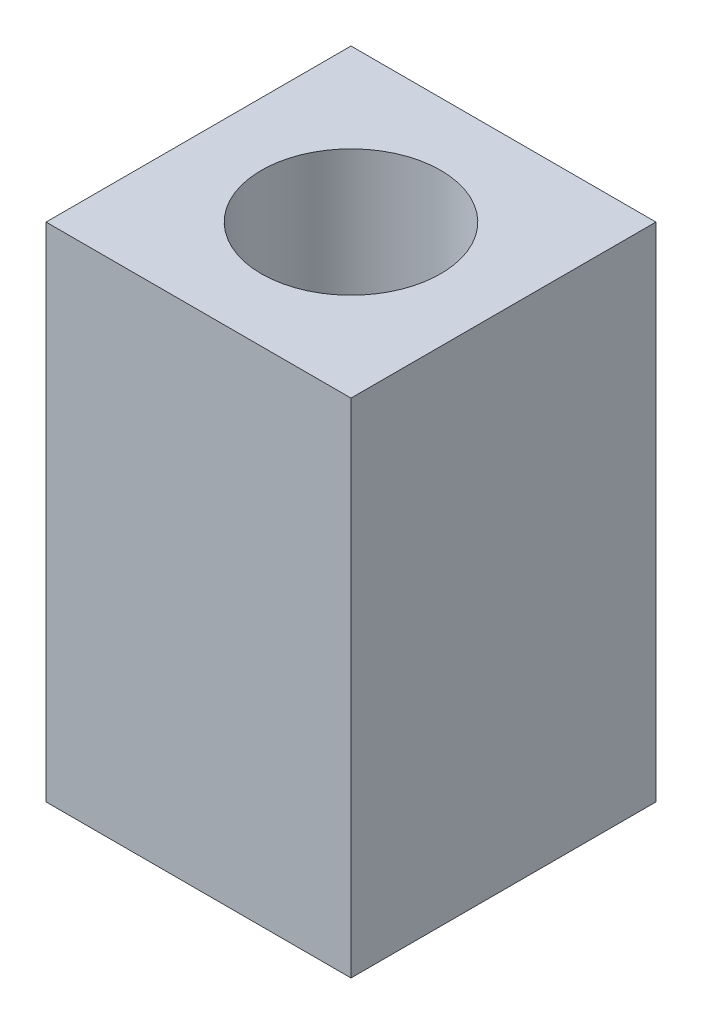
SolidWorks part; units mm, degrees
ref_plane "前视基准面" through (0, 0, 0) normal (0, 0, 1) x (1, 0, 0)
ref_plane "上视基准面" through (0, 0, 0) normal (0, 1, 0) x (1, 0, 0)
ref_plane "右视基准面" through (0, 0, 0) normal (1, 0, 0) x (0, 0, -1)
sketch "草图1" plane through (0, 0, 0) normal (0, 1, 0) x (1, 0, 0)
  line L1 (-42.5, 42.5) -> (42.5, 42.5)
  line L2 (-42.5, 42.5) -> (-42.5, -42.5)
  line L3 (-42.5, -42.5) -> (42.5, -42.5)
  line L4 (42.5, 42.5) -> (42.5, -42.5)
  dimension "D1" = 85
  dimension "D2" = 85
  dimension "D3" = 42.5
  dimension "D4" = 42.5
extrude "凸台-拉伸1" add sketch "草图1" along normal mid plane 140
sketch "草图2" plane through (0, 70, 0) normal (0, 1, 0) x (1, 0, 0)
  circle A0 centre (0, 0) radius 25
  dimension "D1" = 50
extrude "切除-拉伸1" cut sketch "草图2" against normal blind 140
